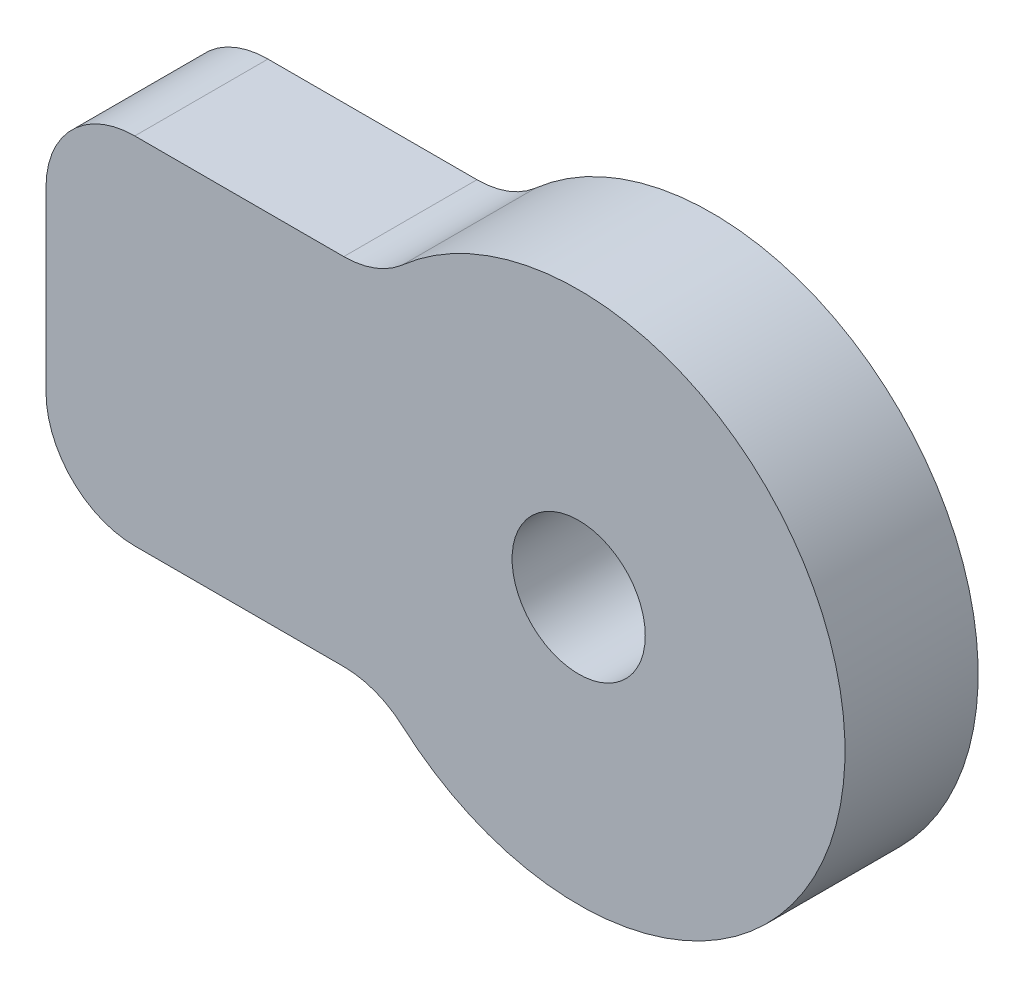
SolidWorks part; units mm, degrees
material "ABS PC"
ref_plane "Front Plane" through (0, 0, 0) normal (0, 0, 1) x (1, 0, 0)
ref_plane "Top Plane" through (0, 0, 0) normal (0, 1, 0) x (1, 0, 0)
ref_plane "Right Plane" through (0, 0, 0) normal (1, 0, 0) x (0, 0, -1)
sketch "Sketch1" plane through (0, 0, 0) normal (0, 0, 1) x (1, 0, 0)
  line L0 (-12, 0) -> (0, 0) construction
  line L1 (-4.4721, 4) -> (-12, 4)
  line L3 (-4.4721, -4) -> (-12, -4)
  line L4 (-12, 4) -> (-12, -4)
  circle A0 centre (0, 0) radius 1.5
  arc A1 (-4.4721, -4) -> (-4.4721, 4) centre (0, 0) ccw
  dimension "D2" = 6
  dimension "D3" = 3
  dimension "D1" = 8
  dimension "D4" = 12
extrude "Boss-Extrude1" add sketch "Sketch1" along normal blind 3
fillet "Fillet1" radius 2 4 edges at (-4.4721, -4, 1.5) (-12, -4, 1.5) (-12, 4, 1.5) (-4.4721, 4, 1.5)
